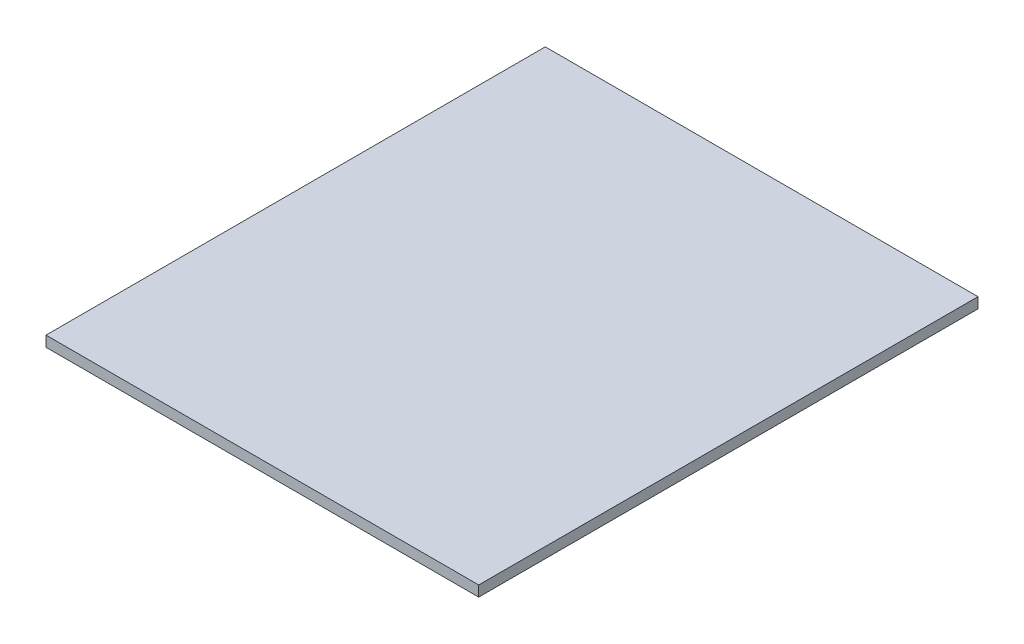
SolidWorks part; units mm, degrees
ref_plane "Front Plane" through (0, 0, 0) normal (0, 0, 1) x (1, 0, 0)
ref_plane "Top Plane" through (0, 0, 0) normal (0, 1, 0) x (1, 0, 0)
ref_plane "Right Plane" through (0, 0, 0) normal (1, 0, 0) x (0, 0, -1)
sketch "Sketch1" plane through (0, 0, 0) normal (0, 1, 0) x (1, 0, 0)
  line L1 (0, 0) -> (130, 0)
  line L2 (0, 0) -> (0, 150)
  line L3 (0, 150) -> (130, 150)
  line L4 (130, 0) -> (130, 150)
  dimension "D1" = 130
  dimension "D2" = 150
extrude "Boss-Extrude1" add sketch "Sketch1" along normal blind 3.175
